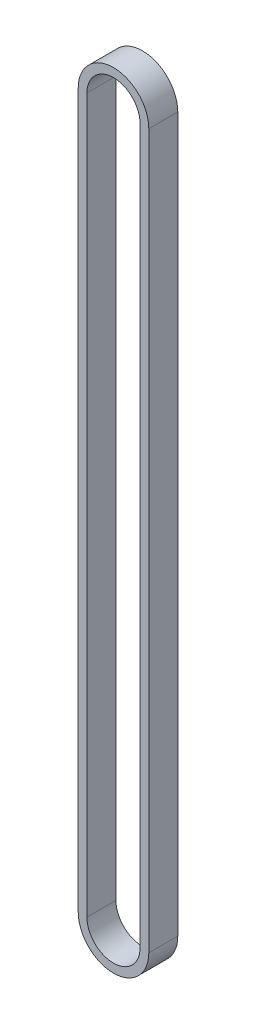
SolidWorks part; units mm, degrees
material "天然橡胶"
ref_plane "前视基准面" through (0, 0, 0) normal (0, 0, 1) x (1, 0, 0)
ref_plane "上视基准面" through (0, 0, 0) normal (0, 1, 0) x (1, 0, 0)
ref_plane "右视基准面" through (0, 0, 0) normal (1, 0, 0) x (0, 0, -1)
other "Configuration Table"
sketch "草图1" plane through (0, 0, 0) normal (0, 0, 1) x (1, 0, 0)
  line L0 (0, -123.1) -> (0, 123.1) construction
  line L1 (-9.17, -123.1) -> (-9.17, 123.1)
  line L2 (9.17, -123.1) -> (9.17, 123.1)
  line L3 (-12.17, -123.1) -> (-12.17, 123.1)
  line L4 (12.17, -123.1) -> (12.17, 123.1)
  arc A0 (-9.17, -123.1) -> (9.17, -123.1) centre (0, -123.1) ccw
  arc A1 (9.17, 123.1) -> (-9.17, 123.1) centre (0, 123.1) ccw
  arc A2 (12.17, 123.1) -> (-12.17, 123.1) centre (0, 123.1) ccw
  arc A3 (-12.17, -123.1) -> (12.17, -123.1) centre (0, -123.1) ccw
  point P2 (0, 0)
  dimension "D2" = 9.17
  dimension "D1" = 246.2
  dimension "D3" = 3
extrude "凸台-拉伸1" add sketch "草图1" along normal blind 10
